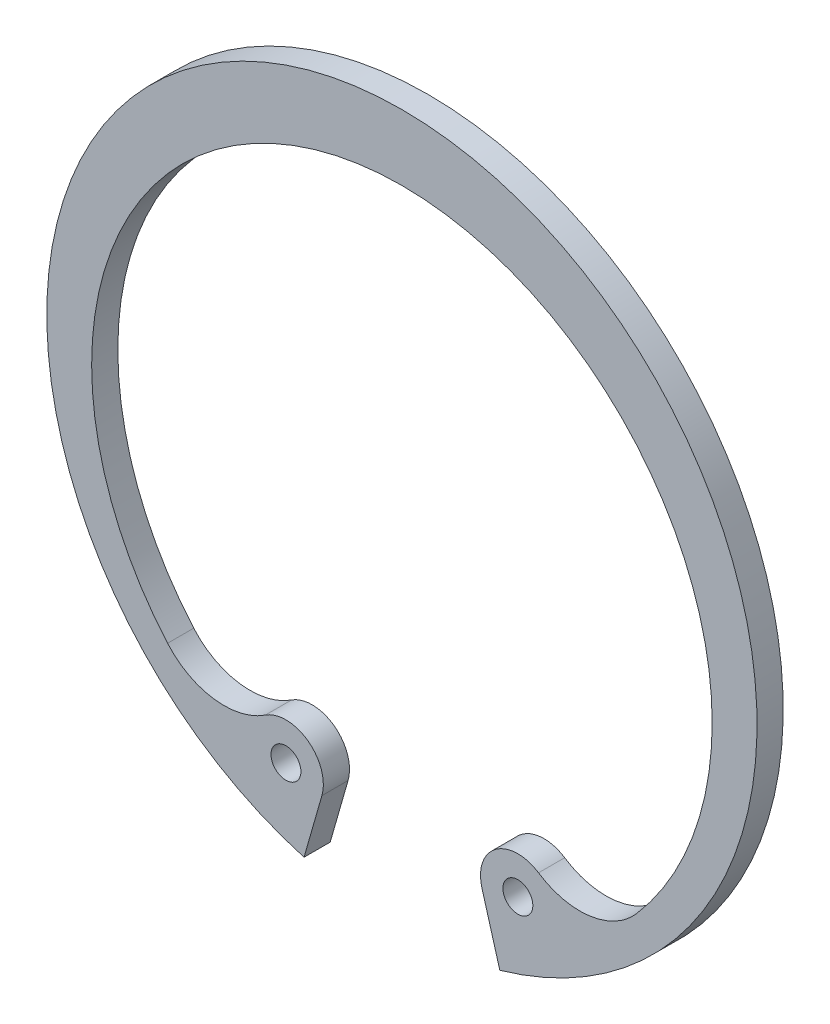
SolidWorks part; units mm, degrees
ref_plane "Front Plane" through (0, 0, 0) normal (0, 0, 1) x (1, 0, 0)
ref_plane "Top Plane" through (0, 0, 0) normal (0, 1, 0) x (1, 0, 0)
ref_plane "Right Plane" through (0, 0, 0) normal (1, 0, 0) x (0, 0, -1)
sketch "Sketch2" plane through (0, 0, 0) normal (0, 0, 1) x (1, 0, 0)
  line L0 (0, 0) -> (0, -23.75) construction
  line L1 (0, 0) -> (6.5464, -22.83)
  line L2 (0, 0) -> (-6.5464, -22.83)
  circle A0 centre (0, 0) radius 23.75
  circle A1 centre (0, -1.4) radius 20.75
  circle A6 centre (-7.7551, -17.9755) radius 2.5
  circle A7 centre (-11.896, -11.7222) radius 5
  circle A9 centre (0, -1.4) radius 15.8
  circle A10 centre (-7.7551, -17.9755) radius 1
  circle A11 centre (7.7551, -17.9755) radius 1
  circle A12 centre (7.7551, -17.9755) radius 2.5
  circle A13 centre (11.896, -11.7222) radius 5
  dimension "D1" = 47.5
  dimension "D5" = 41.5
  dimension "D2" = 10
  dimension "D6" = 5
  dimension "D7" = 31.6
  dimension "D8" = 2
  dimension "D3" = 32
  dimension "D4" = 1.4
extrude "Boss-Extrude1" add sketch "Sketch2" along normal blind 1.75 contours A7 A1 A6 | A1 A6 A10 | A1 A12 L1 A0 L2 A6 | A6 A1 L2 | A1 A12 L1 | A12 A1 A11 | A1 A13 A12 | A1 A6 | A12 A1
equation "\"D1@Sketch2\" = \"G_anneau_alesage_rouleau\""
equation "\"c_anneau\"=31.6"
equation "\"D5@Sketch2\" = \"G_anneau_alesage_rouleau\" - 6"
equation "\"e_anneau\"=1.75"
equation "\"D2@Sketch2\"=2*\"D6@Sketch2\""
equation "\"D7@Sketch2\"=\"c_anneau\""
equation "\"d_ext_rouleau\"= 120"
equation "\"epaisseur_rouleau\"=80"
equation "\"alesage-rouleau\"= 52"
equation "\"jeu_dent_rouleau\"= 2"
equation "\"profondeur_dent_rouleau\"=4"
equation "\"n_dent_roueau\"= 15"
equation "\"d_ext_roulement_rouleau\"= 42"
equation "\"d_int_roulement_rouleau\"= 20"
equation "\"B_roulement_rouleau\"= 12"
equation "\"r_roulement_rouleau\"= 0.6"
equation "\"d_bille_roulement_rouleau\"= 8"
equation "\"F_anneau_alesage_rouleau\"=1.85"
equation "\"G_anneau_alesage_rouleau\"=47.5"
equation "\"K_anneau_alesage_rouleau\"=3.75"
equation "\"d_vis_flasque_rouleau\"=5"
equation "\"l-x_vis_flasque_rouleau\"=4"
equation "\"g_anneau_arbre_rouleau\"=19"
equation "\"f_anneau_arbre_rouleau\"=1.3"
equation "\"k_anneau_arbre_rouleau\"=1.5"
equation "\"h_matrice\"= 15"
equation "\"d_matrice\"= 250"
equation "\"d_granulat\"= 8"
equation "\"zone_vide_matrice\" = 70"
equation "\"d_alesage_matrice\"=50"
equation "\"a_clavette_alesage_matrice\"=16"
equation "\"entrax_vis_rouleau\"=86"
